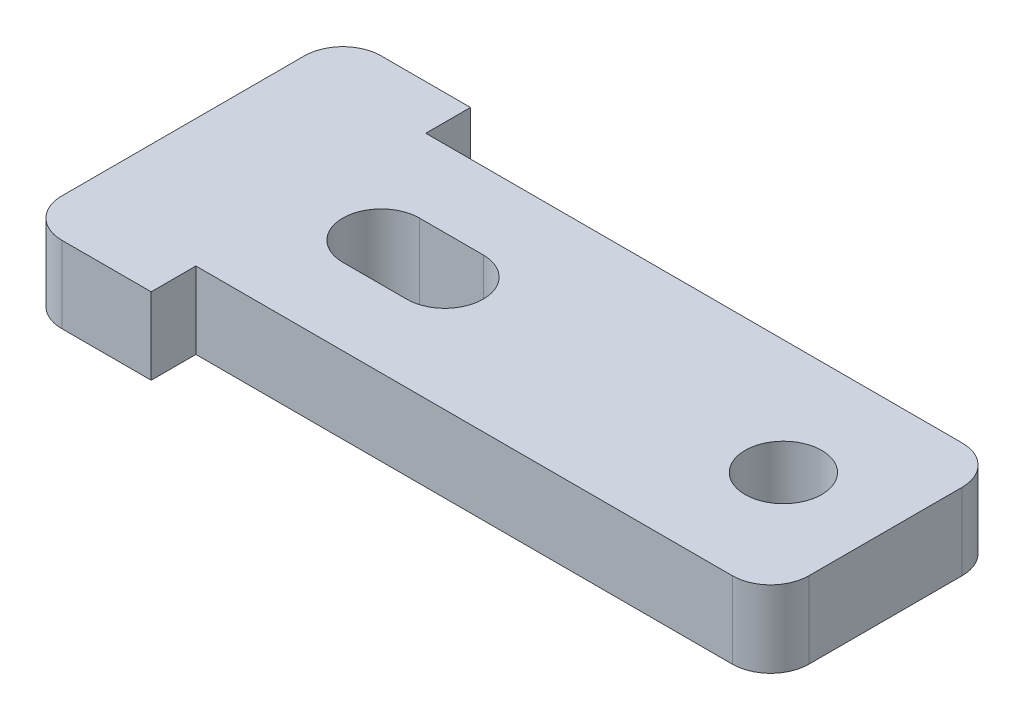
SolidWorks part; units mm, degrees
material "PMMA"
ref_plane "前视基准面" through (0, 0, 0) normal (0, 0, 1) x (1, 0, 0)
ref_plane "上视基准面" through (0, 0, 0) normal (0, 1, 0) x (1, 0, 0)
ref_plane "右视基准面" through (0, 0, 0) normal (1, 0, 0) x (0, 0, -1)
sketch "草图1" plane through (0, 0, 0) normal (0, 1, 0) x (1, 0, 0)
  line L0 (0, 4.75) -> (0, -4.75)
  line L2 (1.5, 6.25) -> (5, 6.25)
  line L3 (5, 6.25) -> (5, 4.5)
  line L4 (5, 4.5) -> (26, 4.5)
  line L5 (27.5, 3) -> (27.5, -3)
  line L6 (26, -4.5) -> (5, -4.5)
  line L7 (5, -4.5) -> (5, -6.25)
  line L8 (5, -6.25) -> (1.5, -6.25)
  line L10 (7.75, 0) -> (10.25, 0) construction
  line L11 (7.75, 1.5) -> (10.25, 1.5)
  line L12 (7.75, -1.5) -> (10.25, -1.5)
  arc A0 (7.75, 1.5) -> (7.75, -1.5) centre (7.75, 0) ccw
  arc A1 (10.25, -1.5) -> (10.25, 1.5) centre (10.25, 0) ccw
  circle A2 centre (23.5, 0) radius 1.5
  arc A3 (27.5, -3) -> (26, -4.5) centre (26, -3) cw
  arc A4 (27.5, 3) -> (26, 4.5) centre (26, 3) ccw
  arc A5 (1.5, -6.25) -> (0, -4.75) centre (1.5, -4.75) cw
  arc A6 (0, 4.75) -> (1.5, 6.25) centre (1.5, 4.75) cw
  point P0 (0, 0)
  point P2 (0, 0)
  point P14 (9, 0)
  point P22 (27.5, -4.5)
  point P25 (27.5, 4.5)
  point P28 (0, -6.25)
  point P31 (0, 6.25)
  dimension "D6" = 1.5
  dimension "D8" = 3
  dimension "D10" = 1.5
  dimension "D1" = 12.5
  dimension "D2" = 9
  dimension "D3" = 5
  dimension "D4" = 22.5
  dimension "D5" = 2.5
  dimension "D7" = 9
  dimension "D9" = 4
extrude "凸台-拉伸1" add sketch "草图1" along normal blind 3
